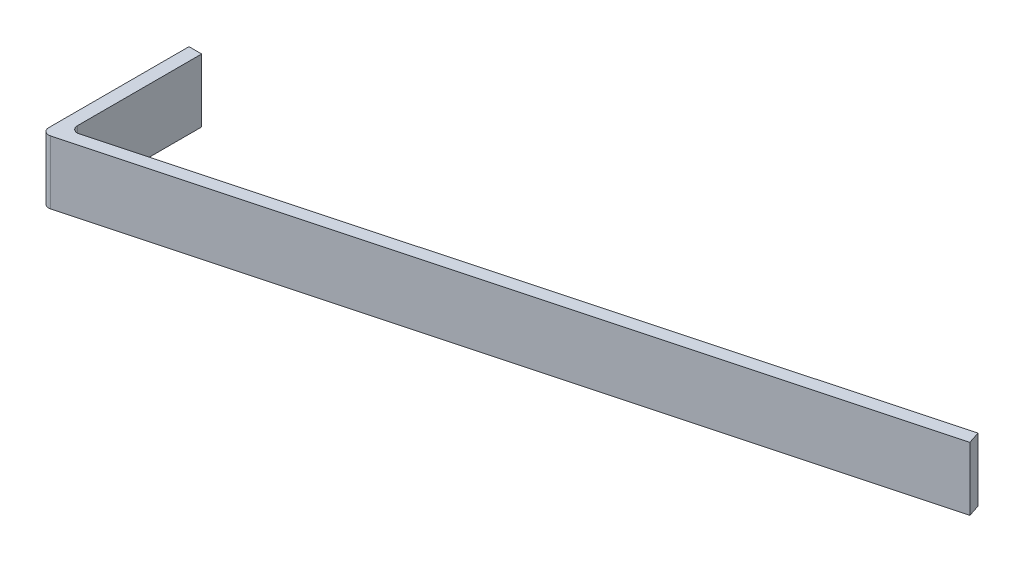
SolidWorks part; units mm, degrees
ref_plane "Front Plane" through (0, 0, 0) normal (0, 0, 1) x (1, 0, 0)
ref_plane "Top Plane" through (0, 0, 0) normal (0, 1, 0) x (1, 0, 0)
ref_plane "Right Plane" through (0, 0, 0) normal (1, 0, 0) x (0, 0, -1)
sketch "Sketch1" plane through (0, 0, 0) normal (0, 1, 0) x (1, 0, 0)
  line L0 (0, 0) -> (2, 0.5359)
  line L2 (0, 0) -> (0, 23.5)
  line L3 (0, 23.5) -> (2, 23.5)
  line L4 (2, 0.5359) -> (2, 23.5)
  dimension "D2" = 23.5
  dimension "D3" = 75
extrude "Boss-Extrude1" add sketch "Sketch1" along normal blind 10
sketch "Sketch3" plane through (0, 0, 0) normal (0, -1, 0) x (1, 0, 0)
  line L0 (0, 0) -> (115.9111, -31.0583)
  line L1 (0, 0) -> (0, -2)
  line L2 (0, -23.5) -> (0, 0) construction
  line L3 (0, -2) -> (115.2858, -32.958)
  line L4 (115.2858, -32.958) -> (115.9111, -31.0583)
  dimension "D1" = 75
  dimension "D2" = 2
  dimension "D3" = 2
extrude "Boss-Extrude2" add sketch "Sketch3" against normal blind 10
fillet "Fillet1" radius 1 2 edges at (0, 5, 0) (2, 5, -2.5371)
